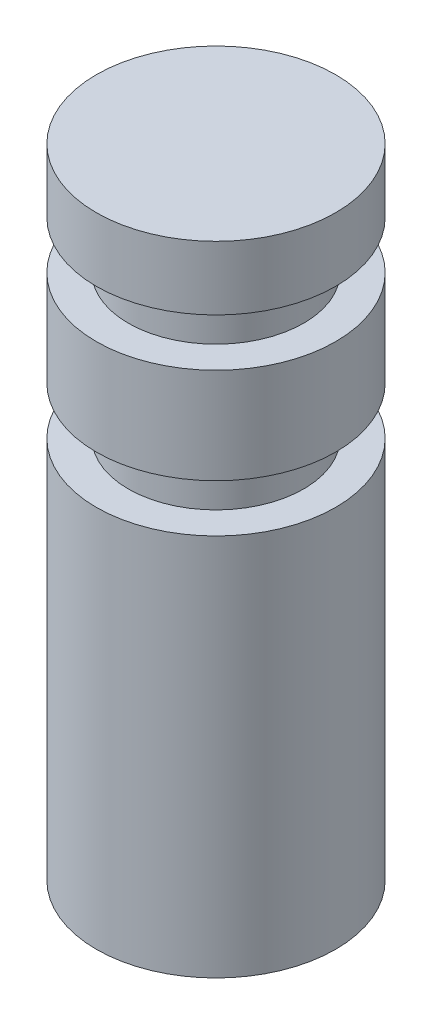
SolidWorks part; units mm, degrees
ref_plane "Front Plane" through (0, 0, 0) normal (0, 0, 1) x (1, 0, 0)
ref_plane "Top Plane" through (0, 0, 0) normal (0, 1, 0) x (1, 0, 0)
ref_plane "Right Plane" through (0, 0, 0) normal (1, 0, 0) x (0, 0, -1)
sketch "Sketch1" plane through (0, 0, 0) normal (0, 1, 0) x (1, 0, 0)
  circle A0 centre (0, 0) radius 4.7625
  dimension "D1" = 9.525
extrude "Boss-Extrude1" add sketch "Sketch1" along normal blind 25.4
sketch "Sketch2" plane through (0, 0, 0) normal (1, 0, 0) x (0, 0, -1)
  line L0 (-9.5731, 19.05) -> (17.3733, 19.05) construction
  line L1 (6.0325, 22.86) -> (3.4925, 22.86)
  line L2 (6.0325, 22.86) -> (6.0325, 20.955)
  line L3 (6.0325, 20.955) -> (3.4925, 20.955)
  line L4 (3.4925, 22.86) -> (3.4925, 20.955)
  line L5 (6.0325, 17.145) -> (3.4925, 17.145)
  line L6 (6.0325, 17.145) -> (6.0325, 15.24)
  line L7 (6.0325, 15.24) -> (3.4925, 15.24)
  line L8 (3.4925, 17.145) -> (3.4925, 15.24)
  line L10 (4.7625, 25.4) -> (-4.7625, 25.4) construction
  dimension "D1" = 6.35
  dimension "D2" = 1.905
  dimension "D3" = 3.4925
  dimension "D4" = 2.54
  dimension "D5" = 3.81
ref_axis "Axis1" through (0, 25.4, 0) along (0, -1, 0)
revolve "Cut-Revolve1" cut sketch "Sketch2" angle 360 about axis through (0, 25.4, 0) along (0, -1, 0)
